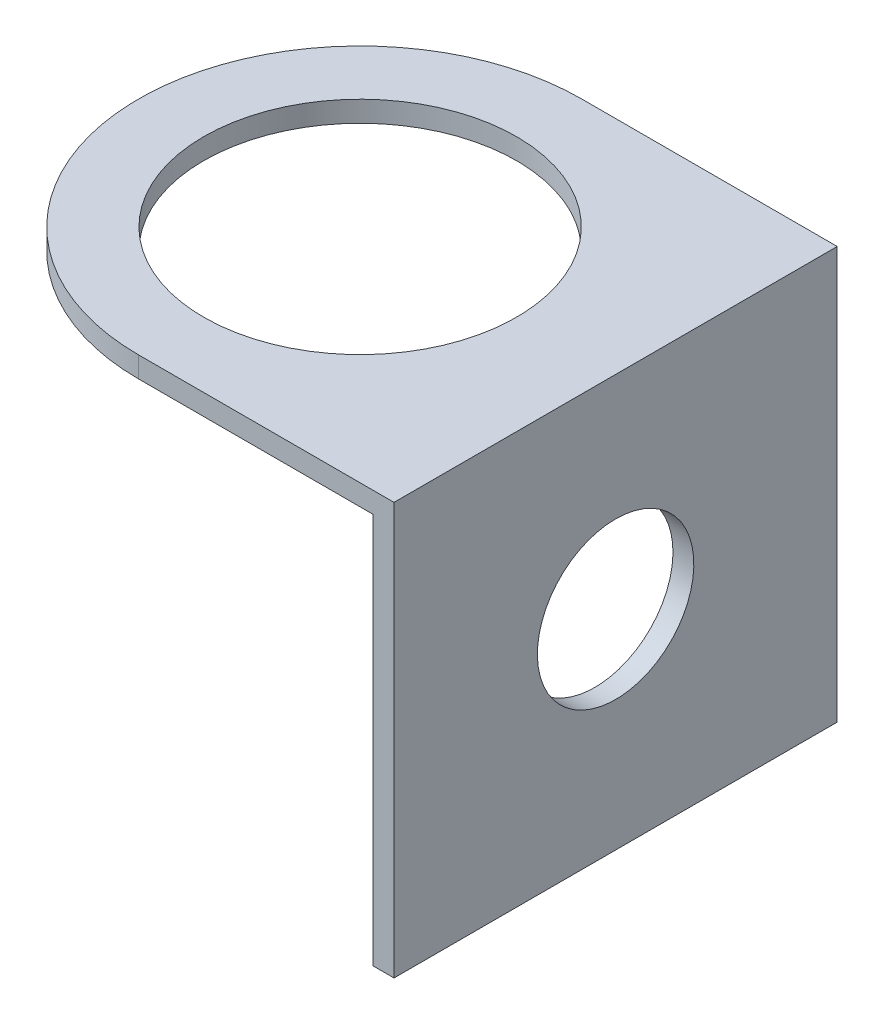
SolidWorks part; units mm, degrees
ref_plane "前视基准面" through (0, 0, 0) normal (0, 0, 1) x (1, 0, 0)
ref_plane "上视基准面" through (0, 0, 0) normal (0, 1, 0) x (1, 0, 0)
ref_plane "右视基准面" through (0, 0, 0) normal (1, 0, 0) x (0, 0, -1)
other "Configuration Table"
sketch "草图1" plane through (0, 0, 0) normal (0, 0, 1) x (1, 0, 0)
  line L0 (-180, 0) -> (0, 0)
  line L1 (0, 0) -> (0, -150)
  line L2 (0, -150) -> (8, -150)
  line L3 (8, -150) -> (8, 8)
  line L4 (8, 8) -> (-180, 8)
  line L5 (-180, 8) -> (-180, 0)
  dimension "D1" = 8
  dimension "D2" = 8
  dimension "D3" = 150
  dimension "D4" = 180
extrude "凸台-拉伸1" add sketch "草图1" along normal blind 170
sketch "草图2" plane through (0, 8, 0) normal (0, 1, 0) x (1, 0, 0)
  line L0 (-216.3195, -85) -> (51.5119, -85) construction
  line L1 (8, -170) -> (-180, -170) construction
  line L2 (8, 0) -> (-180, 0) construction
  line L3 (-180, -170) -> (-180, 0) construction
  line L4 (-90, 0) -> (-180, 0)
  line L5 (-90, -170) -> (-180, -170)
  line L6 (-180, 0) -> (-180, -170)
  circle A0 centre (-90, -85) radius 85 construction
  arc A1 (-90, -170) -> (-90, 0) centre (-90, -85) cw
  circle A2 centre (-90, -85) radius 60
  dimension "D1" = 170
  dimension "D3" = 120
  dimension "D2" = 90
extrude "切除-拉伸1" cut sketch "草图2" against normal blind 180 contours A2 | A1 L4 L6 L5
sketch "草图3" plane through (8, 0, 0) normal (1, 0, 0) x (0, 0, -1)
  line L0 (-85, 25.6845) -> (-85, -173.3318) construction
  line L1 (0, -150) -> (0, 8) construction
  line L2 (-170, -150) -> (-170, 8) construction
  line L4 (0, 0) -> (-209.686, 0) construction
  circle A0 centre (-85, -70) radius 30
  dimension "D1" = 60
  dimension "D2" = 70
extrude "切除-拉伸2" cut sketch "草图3" against normal blind 180 contours A0
